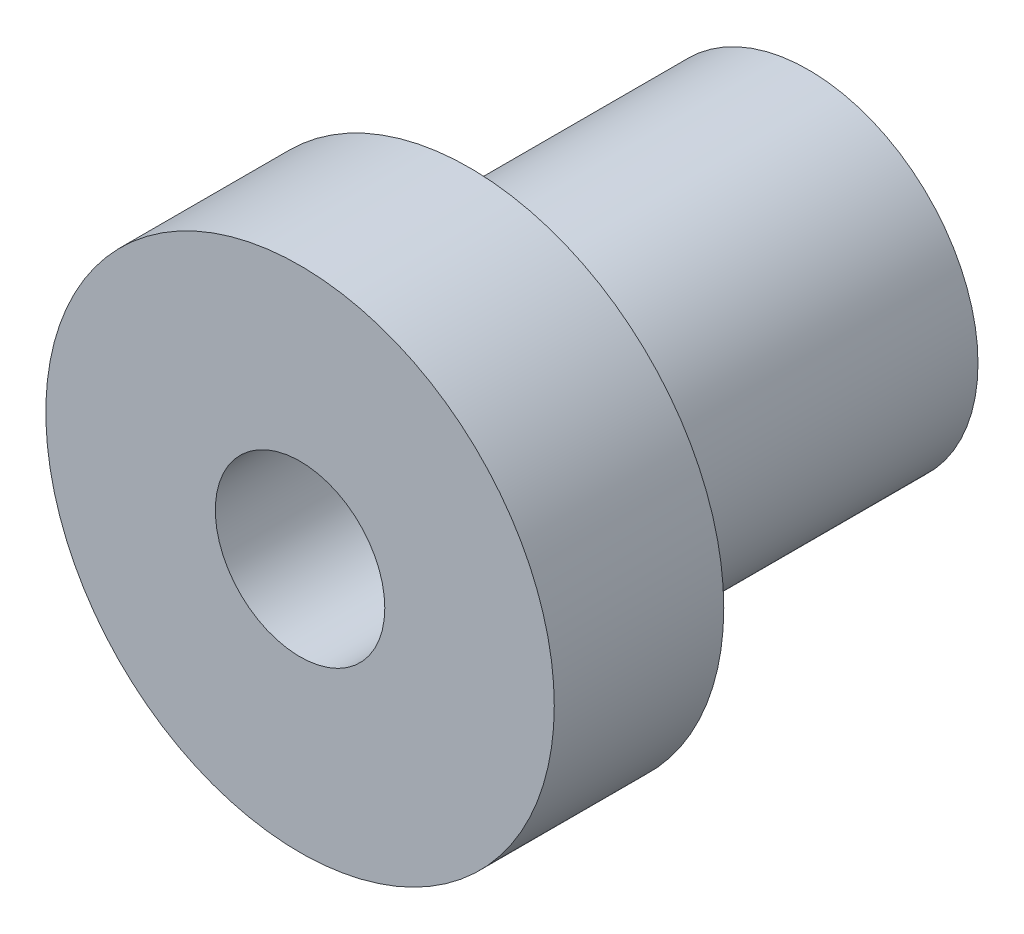
SolidWorks part; units mm, degrees
material "SBR"
ref_plane "Front Plane" through (0, 0, 0) normal (0, 0, 1) x (1, 0, 0)
ref_plane "Top Plane" through (0, 0, 0) normal (0, 1, 0) x (1, 0, 0)
ref_plane "Right Plane" through (0, 0, 0) normal (1, 0, 0) x (0, 0, -1)
sketch "Sketch1" plane through (0, 0, 0) normal (1, 0, 0) x (0, 0, -1)
  line L0 (0, 0) -> (-3.175, 0) construction
  line L1 (0, 0) -> (6.35, 0) construction
  line L3 (-3.175, -1.5875) -> (-3.175, 1.5875) construction
  line L4 (6.35, -3.175) -> (6.35, 3.175) construction
  line L5 (0, -4.7625) -> (0, 4.7625) construction
  point P8 (0, 0)
  point P16 (-3.175, 0)
  point P19 (0, 0)
  point P23 (6.35, 0)
  dimension "Height" = 3.175
  dimension "ID" = 3.175
  dimension "OD" = 9.525
  dimension "Stem Height" = 6.35
  dimension "For ID" = 6.35
sketch "Sketch2" plane through (0, 0, 0) normal (1, 0, 0) x (0, 0, -1)
  line L28 (-3.175, 0) -> (6.35, 0) construction
  line L29 (-3.175, -1.5875) -> (-3.175, 1.5875) construction
  line L30 (6.35, -3.175) -> (6.35, 3.175) construction
  line L31 (-3.175, 1.5875) -> (6.35, 1.5875)
  line L32 (6.35, 1.5875) -> (6.35, 3.175)
  line L33 (6.35, 3.175) -> (0, 3.175)
  line L34 (0, -4.7625) -> (0, 4.7625) construction
  line L35 (0, 3.175) -> (0, 4.7625)
  line L36 (0, 4.7625) -> (-3.175, 4.7625)
  line L37 (-3.175, 4.7625) -> (-3.175, 1.5875)
revolve "Revolve1" add sketch "Sketch2" angle 360 about L28
